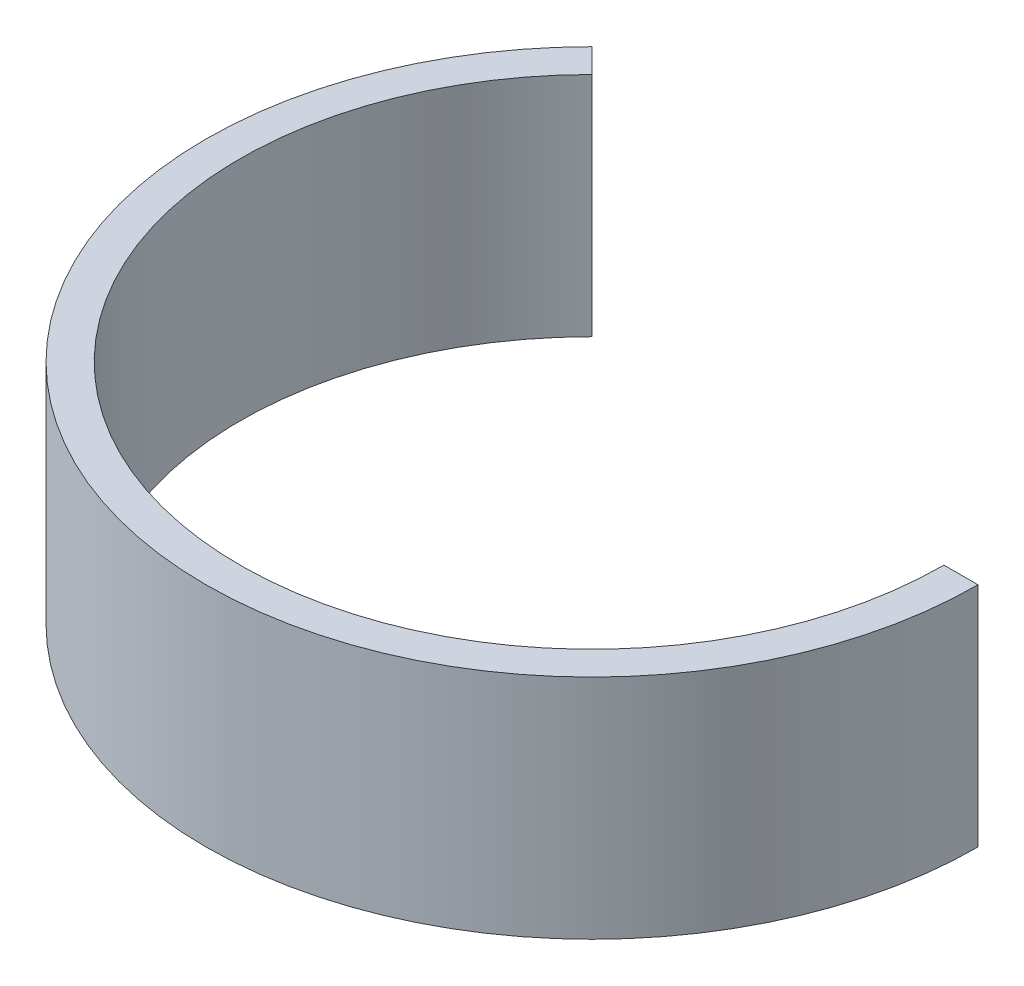
SolidWorks part; units mm, degrees
ref_plane "前基準面" through (0, 0, 0) normal (0, 0, 1) x (1, 0, 0)
ref_plane "上基準面" through (0, 0, 0) normal (0, 1, 0) x (1, 0, 0)
ref_plane "右基準面" through (0, 0, 0) normal (1, 0, 0) x (0, 0, -1)
sketch "草圖1" plane through (0, 0, 0) normal (0, 1, 0) x (1, 0, 0)
  line L0 (15.5, 0) -> (17, 0)
  line L1 (-10.9602, 10.9602) -> (-12.0208, 12.0208)
  arc A0 (-10.9602, 10.9602) -> (15.5, 0) centre (0, 0) ccw
  arc A1 (-12.0208, 12.0208) -> (17, 0) centre (0, 0) ccw
  dimension "D1" = 31
  dimension "D2" = 34
  dimension "D4" = 135
extrude "填料-伸長1" add sketch "草圖1" along normal blind 10 contours A0 L0 A1 L1
